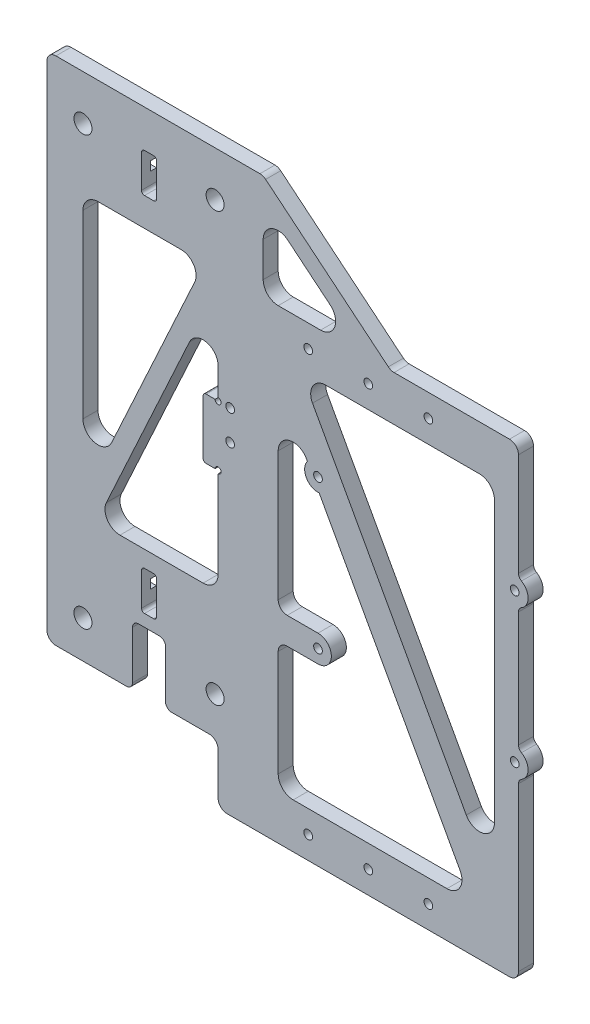
SolidWorks part; units mm, degrees
material "Thornel Mat VMA"
ref_plane "前视基准面" through (0, 0, 0) normal (0, 0, 1) x (1, 0, 0)
ref_plane "上视基准面" through (0, 0, 0) normal (0, 1, 0) x (1, 0, 0)
ref_plane "右视基准面" through (0, 0, 0) normal (1, 0, 0) x (0, 0, -1)
sketch "草图1" plane through (0, 0, 0) normal (0, 0, 1) x (1, 0, 0)
  line L0 (-57, 190) -> (-57, 20)
  line L1 (-57, 20) -> (0, 20)
  line L2 (0, 20) -> (0, 0)
  line L3 (0, 0) -> (100, 0)
  line L4 (100, 0) -> (100, 155)
  line L5 (15, 190) -> (-57, 190)
  line L6 (0, 7.5) -> (100, 7.5) construction
  line L7 (-45, 32.5) -> (-1, 32.5) construction
  line L8 (-45, 32.5) -> (-45, 175) construction
  line L9 (-45, 175) -> (-1, 175) construction
  line L10 (-1, 32.5) -> (-1, 175) construction
  line L11 (-45, 32.5) -> (-1, 175) construction
  line L12 (-45, 175) -> (-1, 32.5) construction
  line L13 (100, 147.5) -> (-57, 147.5) construction
  line L14 (15, 190) -> (15, 155)
  line L15 (15, 155) -> (100, 155)
  line L21 (20, 140) -> (92, 140)
  line L22 (20, 140) -> (20, 15)
  line L23 (20, 15) -> (92, 15)
  line L24 (92, 140) -> (92, 15)
  line L25 (-45, 155) -> (0, 155)
  line L26 (-45, 155) -> (-45, 62.5)
  line L27 (-45, 62.5) -> (0, 62.5)
  line L28 (0, 155) -> (0, 62.5)
  circle A0 centre (-45, 175) radius 3
  circle A1 centre (-1, 175) radius 3
  circle A2 centre (-1, 32.5) radius 3
  circle A3 centre (-45, 32.5) radius 3
  circle A4 centre (30, 7.5) radius 1.45
  circle A5 centre (50, 7.5) radius 1.45
  circle A6 centre (30, 147.5) radius 1.45
  circle A7 centre (50, 147.5) radius 1.45
  circle A8 centre (70, 147.5) radius 1.45
  circle A9 centre (70, 7.5) radius 1.45
  point P8 (-23, 103.75)
  dimension "D4" = 6
  dimension "D7" = 12
  dimension "D8" = 12.5
  dimension "D10" = 2.9
  dimension "D15" = 2.9
  dimension "D28" = 20
  dimension "D29" = 20
  dimension "D1" = 190
  dimension "D2" = 57
  dimension "D3" = 20
  dimension "D5" = 44
  dimension "D6" = 15
  dimension "D9" = 7.5
  dimension "D11" = 30
  dimension "D12" = 20
  dimension "D13" = 30
  dimension "D14" = 20
  dimension "D16" = 140
  dimension "D17" = 100
  dimension "D18" = 7.5
  dimension "D19" = 16
  dimension "D20" = 12
  dimension "D21" = 30
  dimension "D22" = 20
  dimension "D23" = 15
  dimension "D24" = 15
  dimension "D25" = 20
  dimension "D26" = 15
  dimension "D27" = 8
extrude "凸台-拉伸1" add sketch "草图1" along normal blind 5
sketch "草图2" plane through (0, 0, 5) normal (0, 0, 1) x (1, 0, 0)
  line L0 (-45, 175) -> (-1, 175) construction
  line L1 (-45, 32.5) -> (-1, 32.5) construction
  line L2 (-23, 175) -> (-23, 32.5) construction
  line L4 (-25.5, 164.5) -> (-20.5, 164.5)
  line L5 (-25.5, 164.5) -> (-25.5, 177.5)
  line L6 (-25.5, 177.5) -> (-20.5, 177.5)
  line L7 (-20.5, 164.5) -> (-20.5, 177.5)
  line L8 (-25.5, 164.5) -> (-20.5, 177.5) construction
  line L9 (-25.5, 177.5) -> (-20.5, 164.5) construction
  line L10 (-25.5, 57) -> (-20.5, 57)
  line L11 (-25.5, 57) -> (-25.5, 44)
  line L12 (-25.5, 44) -> (-20.5, 44)
  line L13 (-20.5, 57) -> (-20.5, 44)
  line L14 (-25.5, 57) -> (-20.5, 44) construction
  line L15 (-25.5, 44) -> (-20.5, 57) construction
  circle A0 centre (-45, 175) radius 3 construction
  point P9 (-23, 50.5)
  point P12 (-23, 171)
  dimension "D1" = 4
  dimension "D2" = 13
  dimension "D3" = 5
  dimension "D4" = 18
  dimension "D5" = 13
  dimension "D6" = 5
extrude "切除-拉伸1" cut sketch "草图2" against normal through all contours L5 L4 L7 L6 | L11 L10 L13 L12
sketch "草图3" plane through (0, 0, 5) normal (0, 0, 1) x (1, 0, 0)
  line L0 (-23, 177.5) -> (-23, 164.5) construction
  line L1 (-25.5, 177.5) -> (-20.5, 177.5) construction
  line L2 (-25.5, 164.5) -> (-20.5, 164.5) construction
  line L3 (-23, 57) -> (-23, 44) construction
  line L4 (-25.5, 57) -> (-20.5, 57) construction
  line L5 (-25.5, 44) -> (-20.5, 44) construction
  line L7 (-29, 49) -> (-17, 49)
  line L8 (-29, 49) -> (-29, 52)
  line L9 (-29, 52) -> (-17, 52)
  line L10 (-17, 49) -> (-17, 52)
  line L11 (-29, 49) -> (-17, 52) construction
  line L12 (-29, 52) -> (-17, 49) construction
  line L13 (-29, 169.5) -> (-17, 169.5)
  line L14 (-29, 169.5) -> (-29, 172.5)
  line L15 (-29, 172.5) -> (-17, 172.5)
  line L16 (-17, 169.5) -> (-17, 172.5)
  line L17 (-29, 169.5) -> (-17, 172.5) construction
  line L18 (-29, 172.5) -> (-17, 169.5) construction
  point P12 (-23, 50.5)
  point P17 (-23, 171)
  dimension "D1" = 12
  dimension "D2" = 3
  dimension "D3" = 12
  dimension "D4" = 3
extrude "切除-拉伸2" cut sketch "草图3" along normal blind 2 from surface at -5 starting at face at (71.45, 7.5, 0)
sketch "草图4" plane through (0, 0, 0) normal (0, 0, 1) x (1, 0, 0)
  line L0 (-4.5234, 155) -> (-45, 67.0234)
  line L1 (0, 155) -> (-45, 155) construction
  line L2 (-45, 155) -> (-45, 62.5) construction
  line L3 (-45, 67.0234) -> (-45, 62.5)
  line L4 (-45, 62.5) -> (-40.4766, 62.5)
  line L5 (-45, 62.5) -> (0, 62.5) construction
  line L6 (-40.4766, 62.5) -> (0, 150.4766)
  line L7 (0, 62.5) -> (0, 155) construction
  line L8 (0, 150.4766) -> (0, 155)
  line L9 (0, 155) -> (-4.5234, 155)
  line L10 (20, 140) -> (20, 132.6361)
  line L11 (20, 140) -> (20, 15) construction
  line L12 (20, 132.6361) -> (84.6361, 15)
  line L13 (20, 15) -> (92, 15) construction
  line L14 (84.6361, 15) -> (92, 15)
  line L15 (92, 15) -> (92, 22.3639)
  line L16 (92, 22.3639) -> (27.3639, 140)
  line L17 (92, 140) -> (20, 140) construction
  line L18 (27.3639, 140) -> (20, 140)
  line L19 (15, 190) -> (57.5, 155)
  line L20 (100, 155) -> (15, 155) construction
  line L21 (57.5, 155) -> (48.0617, 155)
  line L22 (48.0617, 155) -> (15, 182.2273)
  line L23 (15, 155) -> (15, 190) construction
  line L24 (15, 182.2273) -> (15, 190)
  dimension "D1" = 6
  dimension "D2" = 10
  dimension "D3" = 6
extrude "凸台-拉伸2" add sketch "草图4" along normal up to surface (5 mm away) up to face at (-23, 50.5, 5)
fillet "圆角1" radius 5 15 edges at (27.3639, 140, 2.5) (92, 22.3639, 2.5) (92, 140, 2.5) (84.6361, 15, 2.5) (20, 132.6361, 2.5) (20, 15, 2.5) (0, 150.4766, 2.5) (-40.4766, 62.5, 2.5) (0, 62.5, 2.5) (-4.5234, 155, 2.5) (-45, 67.0234, 2.5) (-45, 155, 2.5) (15, 182.2273, 2.5) (48.0617, 155, 2.5) (15, 155, 2.5)
fillet "圆角2" radius 3 8 edges at (100, 155, 2.5) (100, 0, 2.5) (0, 0, 2.5) (0, 20, 2.5) (-57, 190, 2.5) (15, 190, 2.5) (57.5, 155, 2.5) (-57, 20, 2.5)
sketch "草图5" plane through (0, 0, 5) normal (0, 0, 1) x (1, 0, 0)
  line L1 (33.25, 62.75) -> (98.75, 62.75) construction
  line L2 (33.25, 62.75) -> (33.25, 112.25) construction
  line L3 (33.25, 112.25) -> (98.75, 112.25) construction
  line L4 (98.75, 62.75) -> (98.75, 112.25) construction
  line L5 (33.25, 62.75) -> (98.75, 112.25) construction
  line L6 (33.25, 112.25) -> (98.75, 62.75) construction
  circle A0 centre (50, 147.5) radius 1.45 construction
  circle A1 centre (98.75, 112.25) radius 1.45
  circle A2 centre (98.75, 62.75) radius 1.45
  circle A3 centre (33.25, 112.25) radius 1.45
  circle A4 centre (33.25, 62.75) radius 1.45
  point P0 (66, 87.5)
  dimension "D5" = 2.9
  dimension "D1" = 65.5
  dimension "D2" = 49.5
  dimension "D3" = 60
  dimension "D4" = 16
extrude "切除-拉伸3" cut sketch "草图5" against normal through all
sketch "草图6" plane through (0, 0, 0) normal (0, 0, 1) x (1, 0, 0)
  line L0 (33.25, 67.2) -> (20, 67.2)
  line L1 (20, 67.2) -> (20, 58.3)
  line L2 (20, 58.3) -> (33.25, 58.3)
  line L3 (20, 113.1531) -> (20, 20) construction
  arc A0 (33.25, 58.3) -> (33.25, 67.2) centre (33.25, 62.75) ccw
  circle A1 centre (33.25, 62.75) radius 1.45
  circle A2 centre (33.25, 62.75) radius 1.45
  circle A3 centre (33.25, 112.25) radius 1.45
  circle A4 centre (33.25, 112.25) radius 1.45
  circle A5 centre (98.75, 62.75) radius 1.45
  circle A6 centre (98.75, 62.75) radius 1.45
  circle A7 centre (98.75, 112.25) radius 1.45
  circle A8 centre (98.75, 112.25) radius 1.45
  circle A9 centre (33.25, 112.25) radius 4.45
  circle A10 centre (98.75, 62.75) radius 4.45
  circle A11 centre (98.75, 112.25) radius 4.45
  circle A12 centre (33.25, 62.75) radius 4.45 construction
  dimension "D1" = 0
  dimension "D2" = 0
  dimension "D3" = 0
  dimension "D4" = 0
  dimension "D5" = 3
extrude "凸台-拉伸3" add sketch "草图6" along normal up to surface (5 mm away) up to face at (35.58, 90.5, 5)
sketch "草图7" plane through (0, 0, 0) normal (0, 0, 1) x (1, 0, 0)
  line L0 (0, 67.5) -> (0, 127.6464) construction
  line L1 (0, 117.5) -> (-5, 117.5)
  line L2 (0, 117.5) -> (0, 97.5)
  line L3 (0, 97.5) -> (-5, 97.5)
  line L4 (-5, 117.5) -> (-5, 97.5)
  circle A0 centre (30, 147.5) radius 1.45 construction
  circle A1 centre (30, 7.5) radius 1.45 construction
  dimension "D3" = 90
  dimension "D1" = 5
  dimension "D2" = 30
extrude "凸台-拉伸4" add sketch "草图7" along normal up to surface (5 mm away) up to face at (100.2, 62.75, 5)
sketch "草图8" plane through (0, 0, 5) normal (0, 0, 1) x (1, 0, 0)
  line L0 (4, 117.5) -> (4, 107.5) construction
  line L1 (0, 117.5) -> (0, 127.6464) construction
  line L2 (-5, 97.5) -> (0, 97.5) construction
  circle A0 centre (4, 117.5) radius 1.45
  circle A1 centre (4, 107.5) radius 1.45
  dimension "D3" = 2.9
  dimension "D1" = 4
  dimension "D2" = 10
  dimension "D4" = 10
extrude "切除-拉伸4" cut sketch "草图8" against normal through all
fillet "圆角3" radius 3 2 edges at (20, 58.3, 2.5) (20, 67.2, 2.5)
sketch "草图9" plane through (0, 0, 5) normal (0, 0, 1) x (1, 0, 0)
  circle A0 centre (0, 117.5) radius 1
  circle A1 centre (0, 97.5) radius 1
  dimension "D1" = 2
extrude "切除-拉伸5" cut sketch "草图9" against normal through all
fillet "圆角4" radius 1 2 edges at (-5, 97.5, 2.5) (-5, 117.5, 2.5)
fillet "圆角5" radius 1 16 edges at (-20.5, 44, 2.5) (-25.5, 44, 2.5) (-29, 49, 1) (-29, 52, 1) (-25.5, 57, 2.5) (-20.5, 57, 2.5) (-17, 49, 1) (-17, 52, 1) (-20.5, 164.5, 2.5) (-25.5, 164.5, 2.5) (-29, 169.5, 1) (-29, 172.5, 1) (-25.5, 177.5, 2.5) (-20.5, 177.5, 2.5) (-17, 169.5, 1) (-17, 172.5, 1)
sketch "草图10" plane through (0, 0, 5) normal (0, 0, 1) x (1, 0, 0)
  line L0 (-54, 20) -> (-3, 20) construction
  line L1 (-28.5, 20) -> (-17.5, 20)
  line L2 (-28.5, 20) -> (-28.5, 40)
  line L3 (-28.5, 40) -> (-17.5, 40)
  line L4 (-17.5, 20) -> (-17.5, 40)
  line L5 (-25.5, 56) -> (-25.5, 45) construction
  line L6 (-20.5, 56) -> (-20.5, 45) construction
  dimension "D1" = 20
  dimension "D2" = 3
  dimension "D3" = 3
extrude "切除-拉伸6" cut sketch "草图10" against normal blind 10
fillet "圆角6" radius 2 8 edges at (-17.5, 40, 2.5) (-17.5, 20, 2.5) (100, 58.4792, 2.5) (100, 67.0208, 2.5) (100, 107.9792, 2.5) (100, 116.5208, 2.5) (-28.5, 40, 2.5) (-28.5, 20, 2.5)
